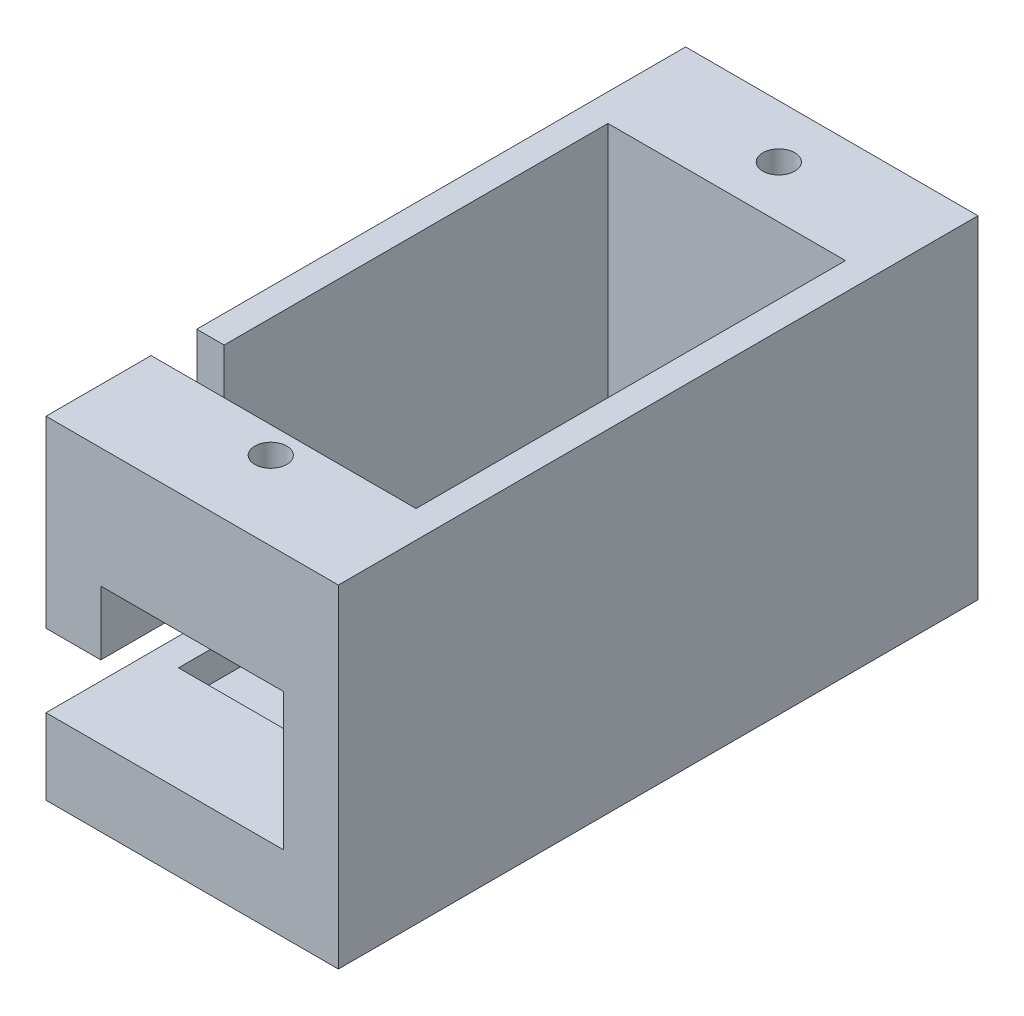
SolidWorks part; units mm, degrees
ref_plane "Front" through (0, 0, 0) normal (0, 0, 1) x (1, 0, 0)
ref_plane "Top" through (0, 0, 0) normal (0, 1, 0) x (1, 0, 0)
ref_plane "Right" through (0, 0, 0) normal (1, 0, 0) x (0, 0, -1)
sketch "Sketch1" plane through (0, 0, 0) normal (0, 1, 0) x (1, 0, 0)
  line L1 (-8, -17.5) -> (8, -17.5)
  line L2 (-8, -17.5) -> (-8, 17.5)
  line L3 (-8, 17.5) -> (8, 17.5)
  line L4 (8, -17.5) -> (8, 17.5)
  line L5 (-8, -17.5) -> (8, 17.5) construction
  line L6 (-8, 17.5) -> (8, -17.5) construction
  point P0 (0, 0)
  dimension "D1" = 16
  dimension "D2" = 35
extrude "Boss-Extrude1" add sketch "Sketch1" along normal blind 18.2
sketch "Sketch2" plane through (0, 18.2, 0) normal (0, 1, 0) x (1, 0, 0)
  line L1 (-6.5, -11.75) -> (6.5, -11.75)
  line L2 (-6.5, -11.75) -> (-6.5, 11.75)
  line L3 (-6.5, 11.75) -> (6.5, 11.75)
  line L4 (6.5, -11.75) -> (6.5, 11.75)
  line L5 (-6.5, -11.75) -> (6.5, 11.75) construction
  line L6 (-6.5, 11.75) -> (6.5, -11.75) construction
  point P0 (0, 0)
  dimension "D1" = 23.5
  dimension "D2" = 13
extrude "Cut-Extrude1" cut sketch "Sketch2" against normal blind 15.7 contours L3 L4 L1 L2
sketch "Sketch3" plane through (0, 18.2, 0) normal (0, 1, 0) x (1, 0, 0)
  line L0 (0, -11.75) -> (0, -13.2) construction
  line L1 (-6.5, -11.75) -> (6.5, -11.75) construction
  line L2 (0, 11.75) -> (0, 14.6) construction
  line L3 (-6.5, 11.75) -> (6.5, 11.75) construction
  circle A0 centre (0, -13.2) radius 0.875
  circle A1 centre (0, 14.6) radius 0.875
  dimension "D2" = 1.75
  dimension "D4" = 1.75
  dimension "D1" = 1.45
  dimension "D3" = 2.85
extrude "Cut-Extrude2" cut sketch "Sketch3" against normal blind 5
sketch "Sketch4" plane through (0, 0, 11.75) normal (0, 0, -1) x (-1, 0, 0)
  line L0 (0, 18.2) -> (0, 11.65) construction
  line L1 (6.5, 18.2) -> (-6.5, 18.2) construction
  line L2 (-5, 11.65) -> (5, 11.65)
  line L3 (-5, 11.65) -> (-5, 4.15)
  line L4 (-5, 4.15) -> (5, 4.15)
  line L5 (5, 4.15) -> (5, 11.65)
  point P7 (0, 11.65)
  dimension "D1" = 6.55
  dimension "D2" = 10
  dimension "D3" = 7.5
extrude "Cut-Extrude3" cut sketch "Sketch4" against normal up to surface (5.75 mm away) up to face at (0, 9.1, 17.5)
sketch "Sketch5" plane through (-8, 0, 0) normal (-1, 0, 0) x (0, 0, 1)
  line L0 (-17.5, 18.2) -> (17.5, 18.2) construction
  line L1 (11.75, 18.2) -> (9.25, 18.2)
  line L2 (11.75, 18.2) -> (11.75, 5.7)
  line L3 (11.75, 5.7) -> (9.25, 5.7)
  line L4 (9.25, 18.2) -> (9.25, 5.7)
  dimension "D1" = 2.5
  dimension "D2" = 12.5
extrude "Cut-Extrude4" cut sketch "Sketch5" against normal up to surface (1.5 mm away) up to face at (-6.5, 10.35, 0)
sketch "Sketch6" plane through (-8, 0, 0) normal (-1, 0, 0) x (0, 0, 1)
  line L0 (17.5, 18.2) -> (17.5, 0) construction
  line L1 (9.25, 4.15) -> (17.5, 4.15)
  line L2 (9.25, 4.15) -> (9.25, 8.15)
  line L3 (9.25, 8.15) -> (17.5, 8.15)
  line L4 (17.5, 4.15) -> (17.5, 8.15)
  line L5 (17.5, 4.15) -> (11.75, 4.15) construction
  line L6 (9.25, 18.2) -> (9.25, 5.7) construction
  dimension "D1" = 4
extrude "Cut-Extrude5" cut sketch "Sketch6" against normal up to surface (3 mm away) up to face at (-5, 7.9, 14.625)
